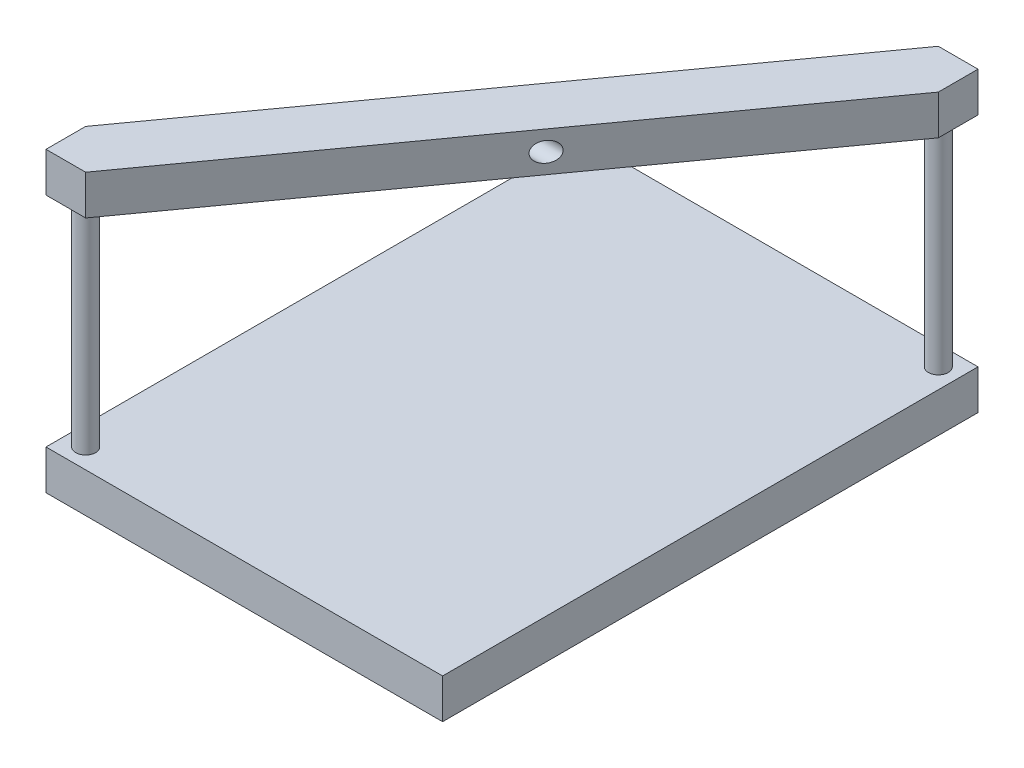
SolidWorks part; units mm, degrees
ref_plane "Front Plane" through (0, 0, 0) normal (0, 0, 1) x (1, 0, 0)
ref_plane "Top Plane" through (0, 0, 0) normal (0, 1, 0) x (1, 0, 0)
ref_plane "Right Plane" through (0, 0, 0) normal (1, 0, 0) x (0, 0, -1)
sketch "Sketch1" plane through (0, 0, 0) normal (0, 1, 0) x (1, 0, 0)
  line L1 (0, 0) -> (100, 0)
  line L2 (0, 0) -> (0, 135)
  line L3 (0, 135) -> (100, 135)
  line L4 (100, 0) -> (100, 135)
  dimension "D1" = 135
  dimension "D2" = 100
extrude "BottomPlate" add sketch "Sketch1" along normal blind 10
sketch "Sketch2" plane through (0, 10, 0) normal (0, 1, 0) x (1, 0, 0)
  line L0 (100, 0) -> (100, 135) construction
  line L1 (100, 135) -> (0, 135) construction
  line L2 (0, 135) -> (0, 0) construction
  line L4 (0, 0) -> (100, 0) construction
  circle A0 centre (95, 130) radius 2.5
  circle A1 centre (5, 5) radius 2.5
  point P8 (0, 0)
  point P13 (13.5283, 0)
  dimension "D1" = 5
  dimension "D3" = 5
  dimension "D6" = 5
  dimension "D2" = 5
  dimension "D4" = 5
  dimension "D5" = 5
extrude "TopPlatformSupport" add sketch "Sketch2" along normal blind 55
sketch "Sketch3" plane through (0, 65, 0) normal (0, 1, 0) x (1, 0, 0)
  line L0 (90, 135) -> (0, 10)
  line L1 (0, 0) -> (10, 0)
  line L2 (0, 0) -> (0, 10)
  line L3 (90, 135) -> (100, 135)
  line L4 (100, 125) -> (100, 135)
  line L5 (10, 0) -> (100, 125)
  dimension "D1" = 10
  dimension "D2" = 10
  dimension "D3" = 10
  dimension "D4" = 10
extrude "TopThreadedRodPlatform" add sketch "Sketch3" along normal blind 10
sketch "Sketch5" plane through (100, 0, 0) normal (1, 0, 0) x (0, 0, -1)
  line L0 (0, 70) -> (135, 70) construction
  line L1 (0, 75) -> (0, 65) construction
  line L2 (135, 75) -> (135, 65) construction
  circle A0 centre (67.5, 70) radius 2.5
  dimension "D1" = 5
extrude "Cut-Extrude2" cut sketch "Sketch5" against normal up to next
